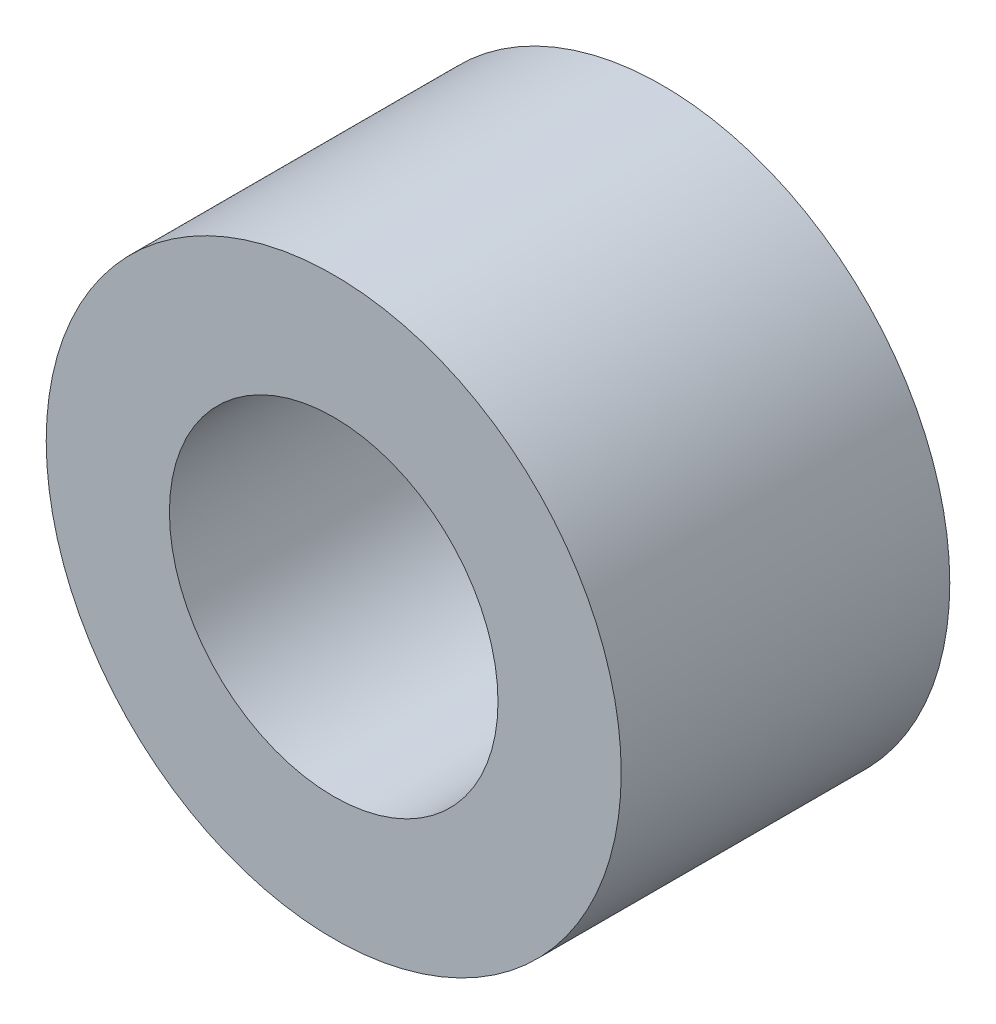
SolidWorks part; units mm, degrees
material "AISI 304"
ref_plane "前视基准面" through (0, 0, 0) normal (0, 0, 1) x (1, 0, 0)
ref_plane "上视基准面" through (0, 0, 0) normal (0, 1, 0) x (1, 0, 0)
ref_plane "右视基准面" through (0, 0, 0) normal (1, 0, 0) x (0, 0, -1)
other "Configuration Table"
sketch "草图1" plane through (0, 0, 0) normal (0, 0, 1) x (1, 0, 0)
  line L0 (-5.037, 0) -> (4.0741, 0) construction
  line L1 (0, 2.9259) -> (0, -3.9259) construction
  circle A0 centre (0, 0) radius 2
  circle A1 centre (0, 0) radius 3.5
  dimension "D1" = 4
  dimension "D2" = 7
extrude "凸台-拉伸1" add sketch "草图1" along normal blind 4
